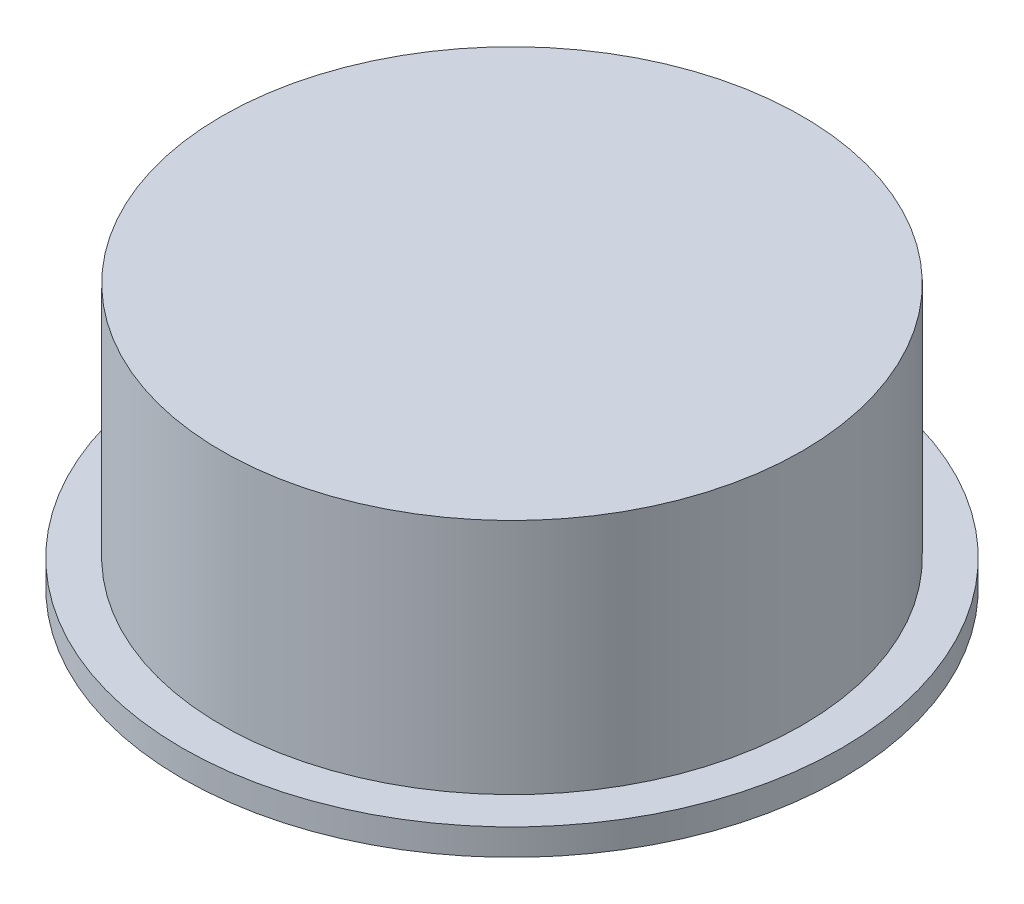
SolidWorks part; units mm, degrees
ref_plane "Front Plane" through (0, 0, 0) normal (0, 0, 1) x (1, 0, 0)
ref_plane "Top Plane" through (0, 0, 0) normal (0, 1, 0) x (1, 0, 0)
ref_plane "Right Plane" through (0, 0, 0) normal (1, 0, 0) x (0, 0, -1)
sketch "Sketch3" plane through (0, 0, 0) normal (0, 0, 1) x (1, 0, 0)
  line L0 (-37.5, 0) -> (-30, 0)
  line L1 (-30, 0) -> (-30, 27)
  line L2 (-30, 27) -> (0, 27)
  line L3 (0, 27) -> (0, 30)
  line L4 (0, 30) -> (-33, 30)
  line L5 (-33, 30) -> (-33, 3)
  line L6 (-33, 3) -> (-37.5, 3)
  line L7 (-37.5, 3) -> (-37.5, 0)
  line L8 (-33, 15.6797) -> (-30, 15.6797) construction
  line L9 (0, 18.1892) -> (0, -49981.8108) construction
  line L10 (-38.3705, 0) -> (49961.6295, 0) construction
  dimension "D1" = 3
  dimension "D2" = 37.5
  dimension "D3" = 30
  dimension "D4" = 27
revolve "Revolve1" add sketch "Sketch3" angle 360 about L9
equation "\"ABS_Thickness\"=3"
equation "\"Rocket_Radius_Internal\"=37.5"
equation "\"Electronics_Cavity_Radius\"=30"
equation "\"Electronics_Cavity_Height\"=27"
